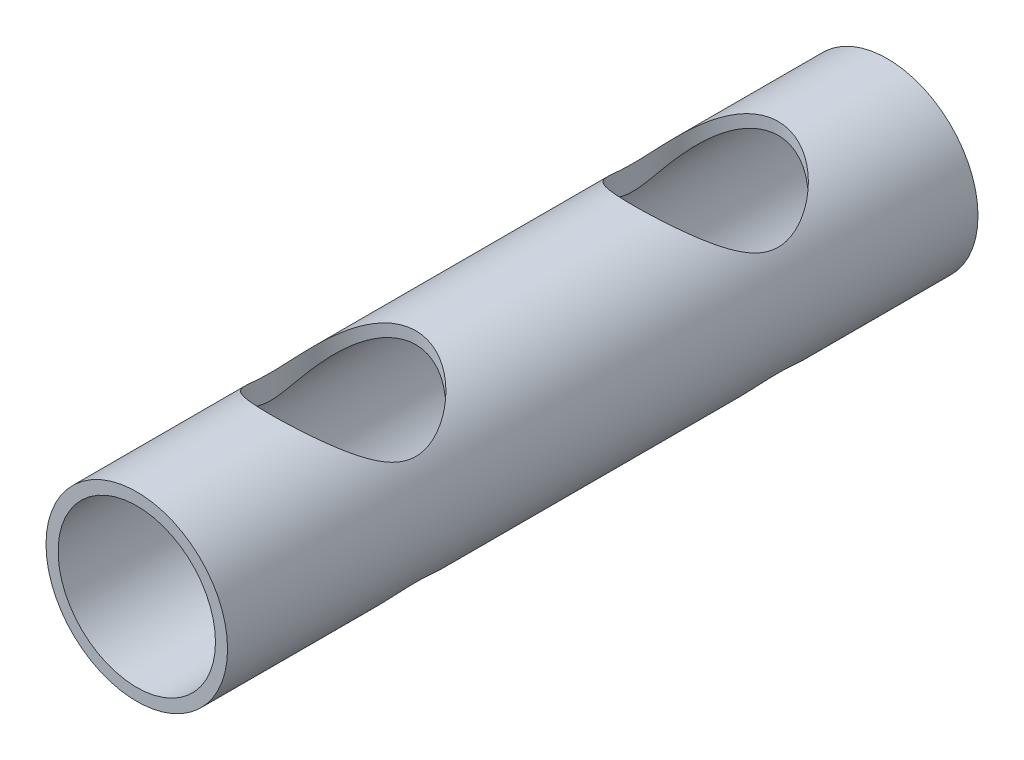
SolidWorks part; units mm, degrees
ref_plane "Front Plane" through (0, 0, 0) normal (0, 0, 1) x (1, 0, 0)
ref_plane "Top Plane" through (0, 0, 0) normal (0, 1, 0) x (1, 0, 0)
ref_plane "Right Plane" through (0, 0, 0) normal (1, 0, 0) x (0, 0, -1)
sketch "Sketch1" plane through (0, 0, 0) normal (0, 0, 1) x (1, 0, 0)
  circle A0 centre (0, 0) radius 7.5
  dimension "D1" = 15
extrude "Boss-Extrude1" add sketch "Sketch1" along normal blind 62
sketch "Sketch2" plane through (0, 0, 62) normal (0, 0, 1) x (1, 0, 0)
  circle A0 centre (0, 0) radius 6.5
  dimension "D1" = 13
extrude "Cut-Extrude1" cut sketch "Sketch2" against normal through all
ref_plane "Plane1" through (0, 7.5, 0) normal (0, 1, 0) x (1, 0, 0)
sketch "Sketch3" plane through (0, 7.5, 0) normal (0, 1, 0) x (1, 0, 0)
  line L0 (0, 0) -> (0, -59.9454) construction
  line L1 (0, -29.9727) -> (-7.4697, -29.9727) construction
  line L2 (0, -29.9727) -> (7.6031, -29.9727) construction
  circle A0 centre (0, -15) radius 6
  circle A1 centre (0, -44.9454) radius 6
  dimension "D2" = 12
  dimension "D1" = 29.9727
  dimension "D3" = 15
extrude "Cut-Extrude2" cut sketch "Sketch3" against normal through all
